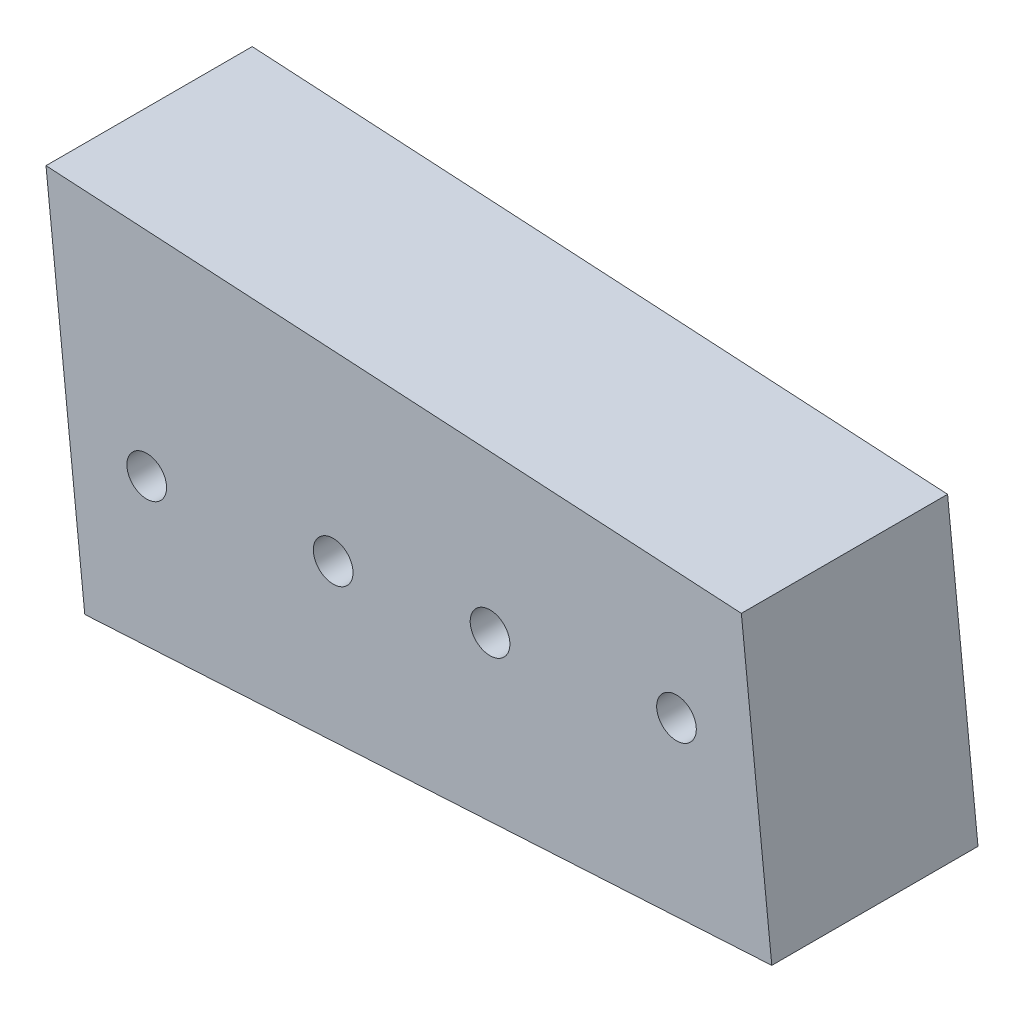
SolidWorks part; units mm, degrees
ref_plane "Alzado" through (0, 0, 0) normal (0, 0, 1) x (1, 0, 0)
ref_plane "Planta" through (0, 0, 0) normal (0, 1, 0) x (1, 0, 0)
ref_plane "Vista lateral" through (0, 0, 0) normal (1, 0, 0) x (0, 0, -1)
sketch "Croquis1" plane through (0, 0, 0) normal (0, 0, 1) x (1, 0, 0)
  line L0 (-34.7523, 0) -> (75.8524, 0) construction
  line L1 (-37.8586, 29.5857) -> (73.4186, 23.1798)
  line L2 (-31.654, -29.5087) -> (78.2862, -23.1798)
  line L3 (73.4186, 23.1798) -> (78.2862, -23.1798)
  line L4 (121.3719, 0) -> (130.5, 0) construction
  line L5 (-31.654, -29.5087) -> (-37.8586, 29.5857)
  line L6 (73.752, -50.6704) -> (67.4867, 9.0016) construction
  line L7 (-20.9673, -60.6155) -> (-27.2326, -0.9435) construction
  line L8 (-33.0059, -16.6322) -> (-25.6663, -15.8615) construction
  line L9 (69.053, -5.9164) -> (76.3927, -5.1457) construction
  line L10 (-27.2326, -0.9435) -> (7.576, 2.7112) construction
  line L11 (67.4867, 9.0016) -> (32.678, 5.3468) construction
  point P6 (125.9359, 0)
  point P7 (75.8524, 0)
  dimension "D1" = 6.589
  dimension "D2" = 46.6145
  dimension "D3" = 59.4192
  dimension "D5" = 110
  dimension "D6" = 15
  dimension "D7" = 15
extrude "Saliente-Extruir1" add sketch "Croquis1" along normal mid plane 33
sketch "Croquis2" plane through (0, 0, 16.5) normal (0, 0, 1) x (1, 0, 0)
  line L0 (78.2862, -23.1798) -> (73.4186, 23.1798) construction
  circle A6 centre (63.0361, 3.5068) radius 3.175
  circle A7 centre (33.2002, 0.3742) radius 3.175
  circle A8 centre (8.0981, -2.2614) radius 3.175
  circle A9 centre (-21.7378, -5.3941) radius 3.175
  point P5 (75.8524, 0)
  dimension "D9" = 6.35
  dimension "D8" = 3.5068
  dimension "D1" = 30
  dimension "D2" = 25.24
  dimension "D3" = 30
  dimension "D4" = 3.1327
  dimension "D5" = 2.6356
  dimension "D6" = 3.1327
  dimension "D7" = 12.38
extrude "Cortar-Extruir1" cut sketch "Croquis2" against normal through all
